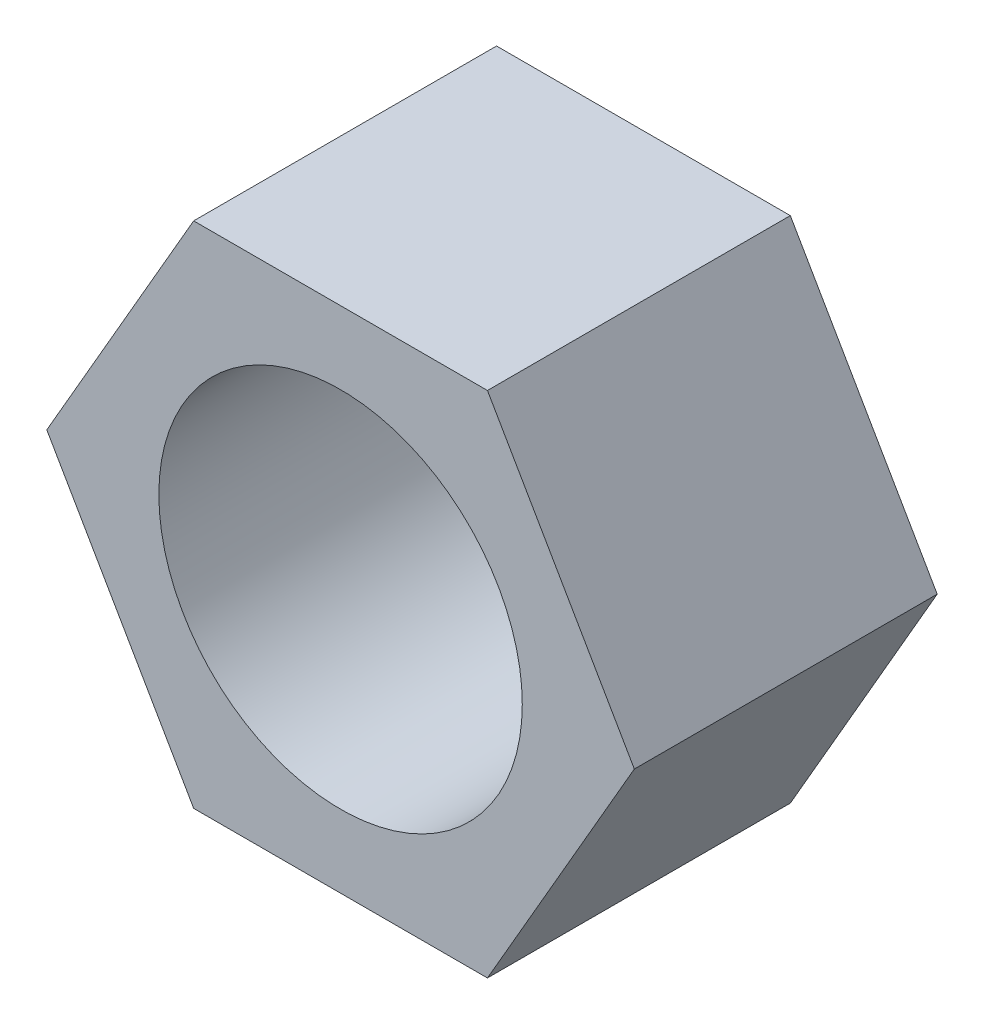
SolidWorks part; units mm, degrees
ref_plane "Front Plane" through (0, 0, 0) normal (0, 0, 1) x (1, 0, 0)
ref_plane "Top Plane" through (0, 0, 0) normal (0, 1, 0) x (1, 0, 0)
ref_plane "Right Plane" through (0, 0, 0) normal (1, 0, 0) x (0, 0, -1)
sketch "Sketch1" plane through (0, 0, 0) normal (0, 0, 1) x (1, 0, 0)
  line L1 (19.1892, 11.6116) -> (17.9768, 13.7116)
  line L2 (17.9768, 13.7116) -> (15.5519, 13.7116)
  line L3 (15.5519, 13.7116) -> (14.3395, 11.6116)
  line L4 (14.3395, 11.6116) -> (15.5519, 9.5116)
  line L5 (15.5519, 9.5116) -> (17.9768, 9.5116)
  line L6 (17.9768, 9.5116) -> (19.1892, 11.6116)
  circle A0 centre (16.7643, 11.6116) radius 1.5
  circle A1 centre (16.7643, 11.6116) radius 2.1 construction
  dimension "D1" = 4.2
extrude "Boss-Extrude1" add sketch "Sketch1" along normal blind 2.5
